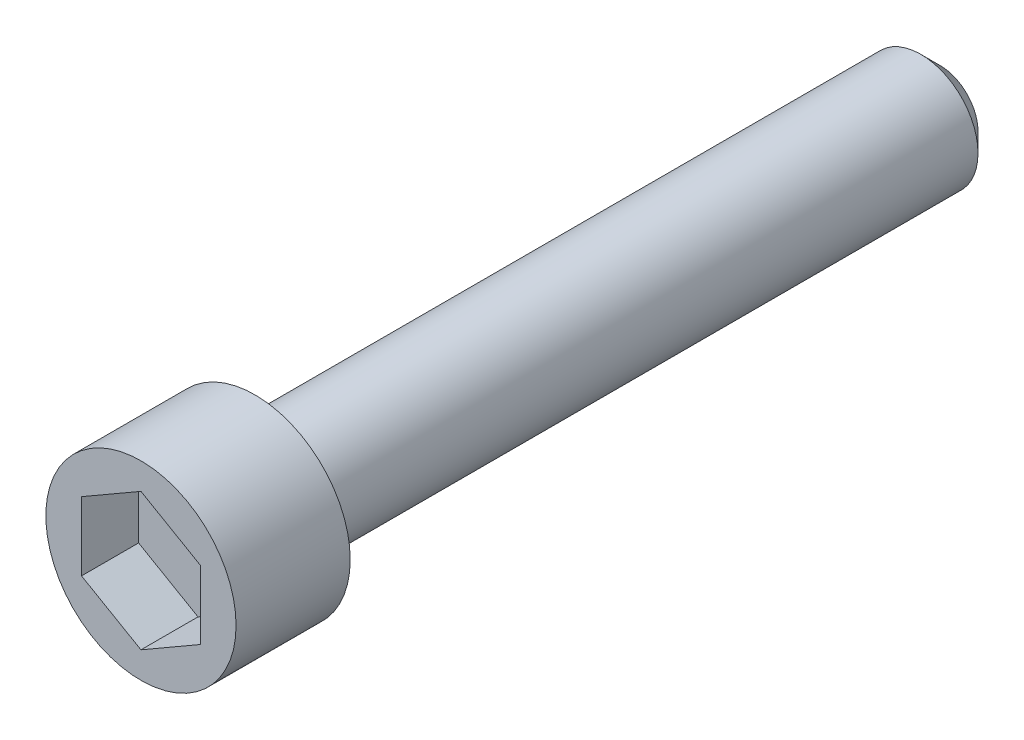
SolidWorks part; units mm, degrees
ref_plane "前视基准面" through (0, 0, 0) normal (0, 0, 1) x (1, 0, 0)
ref_plane "上视基准面" through (0, 0, 0) normal (0, 1, 0) x (1, 0, 0)
ref_plane "右视基准面" through (0, 0, 0) normal (1, 0, 0) x (0, 0, -1)
sketch "草图1" plane through (0, 0, 0) normal (0, 0, 1) x (1, 0, 0)
  circle A0 centre (0, 0) radius 1.5
extrude "凸台-拉伸1" add sketch "草图1" along normal blind 18
sketch "草图2" plane through (0, 0, 18) normal (0, 0, 1) x (1, 0, 0)
  circle A0 centre (0, 0) radius 2.5
extrude "凸台-拉伸2" add sketch "草图2" along normal blind 3
sketch "草图3" plane through (0, 0, 21) normal (0, 0, 1) x (1, 0, 0)
  line L1 (0, 1.8034) -> (-1.5618, 0.9017)
  line L2 (-1.5618, 0.9017) -> (-1.5618, -0.9017)
  line L3 (-1.5618, -0.9017) -> (0, -1.8034)
  line L4 (0, -1.8034) -> (1.5618, -0.9017)
  line L5 (1.5618, -0.9017) -> (1.5618, 0.9017)
  line L6 (1.5618, 0.9017) -> (0, 1.8034)
  circle A0 centre (0, 0) radius 1.5618 construction
extrude "切除-拉伸1" cut sketch "草图3" against normal blind 1.5
chamfer "倒角1" distance 0.5 angle 45 1 edges at (1.5, 0, 0)
